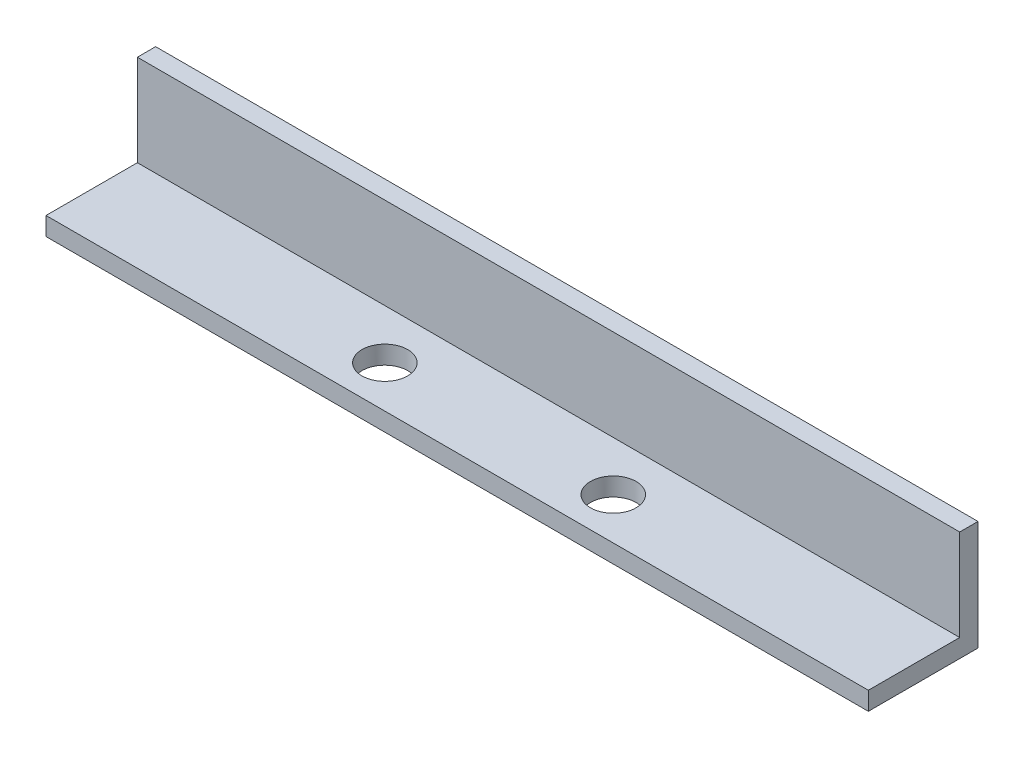
SolidWorks part; units mm, degrees
ref_plane "Front Plane" through (0, 0, 0) normal (0, 0, 1) x (1, 0, 0)
ref_plane "Top Plane" through (0, 0, 0) normal (0, 1, 0) x (1, 0, 0)
ref_plane "Right Plane" through (0, 0, 0) normal (1, 0, 0) x (0, 0, -1)
sketch "Sketch1" plane through (0, 0, 0) normal (0, 1, 0) x (1, 0, 0)
  line L1 (-61.1667, -4.5833) -> (28.8333, -4.5833)
  line L2 (-61.1667, -4.5833) -> (-61.1667, 7.4167)
  line L3 (-61.1667, 7.4167) -> (28.8333, 7.4167)
  line L4 (28.8333, -4.5833) -> (28.8333, 7.4167)
  line L5 (-61.1667, -4.5833) -> (28.8333, 7.4167) construction
  line L6 (-61.1667, 7.4167) -> (28.8333, -4.5833) construction
  point P0 (-16.1667, 1.4167)
  dimension "D1" = 12
  dimension "D2" = 90
extrude "Boss-Extrude1" add sketch "Sketch1" along normal blind 2
sketch "Sketch2" plane through (0, 2, 0) normal (0, 1, 0) x (1, 0, 0)
  line L0 (28.8333, -4.5833) -> (28.8333, 7.4167) construction
  line L1 (-61.1667, 7.4167) -> (28.8333, 7.4167)
  line L2 (-61.1667, 7.4167) -> (-61.1667, 5.4167)
  line L3 (-61.1667, 5.4167) -> (28.8333, 5.4167)
  line L4 (28.8333, 7.4167) -> (28.8333, 5.4167)
  dimension "2" = 2
extrude "Boss-Extrude2" add sketch "Sketch2" along normal blind 10
sketch "Sketch3" plane through (0, 2, 0) normal (0, 1, 0) x (1, 0, 0)
  line L0 (-6.6, 0) -> (6.6, 0) construction
  line L1 (28.8333, -4.5833) -> (28.8333, 5.4167) construction
  circle A0 centre (-28.6667, 0) radius 2.5
  circle A1 centre (-3.6667, 0) radius 2.5
  dimension "D1" = 5
  dimension "D2" = 5
  dimension "D3" = 25
  dimension "D4" = 32.5
extrude "Cut-Extrude1" cut sketch "Sketch3" against normal through all both and the other way through all
